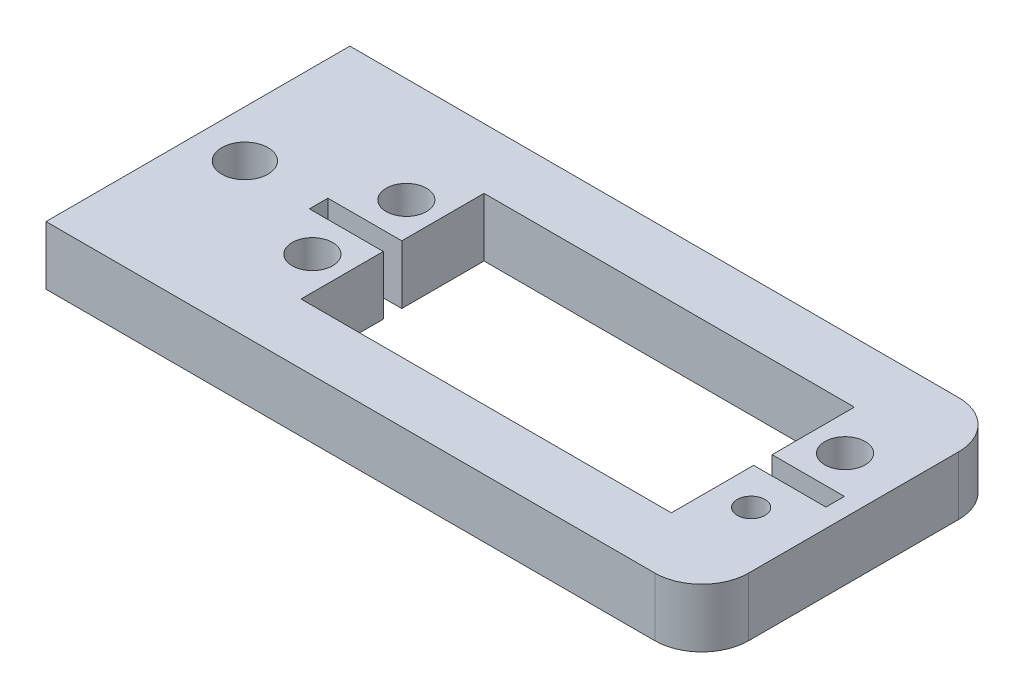
SolidWorks part; units mm, degrees
ref_plane "Front" through (0, 0, 0) normal (0, 0, 1) x (1, 0, 0)
ref_plane "Top" through (0, 0, 0) normal (0, 1, 0) x (1, 0, 0)
ref_plane "Right" through (0, 0, 0) normal (1, 0, 0) x (0, 0, -1)
sketch "Sketch1" plane through (0, 0, 0) normal (0, 1, 0) x (1, 0, 0)
  line L0 (-9.153, -1.4319) -> (-66.073, -1.4319)
  line L1 (-13.9032, -18.8819) -> (-13.9032, -27.7919)
  line L2 (-4.073, -6.5119) -> (-4.073, -29.2519)
  line L3 (-9.153, -34.3319) -> (-66.073, -34.3319)
  line L4 (-13.9032, -27.7919) -> (-54.0032, -27.7919)
  line L5 (-54.0032, -27.7919) -> (-54.0032, -18.8819)
  line L6 (-54.0032, -7.9719) -> (-13.9032, -7.9719)
  line L7 (-13.9032, -7.9719) -> (-13.9032, -16.8819)
  line L8 (-75.073, -29.2519) -> (-75.073, -6.5119)
  line L9 (-13.9032, -16.8819) -> (-6.073, -16.8819)
  line L10 (-54.0032, -16.8819) -> (-62.0032, -16.8819)
  line L11 (-13.9032, -18.8819) -> (-6.073, -18.8819)
  line L12 (-62.0032, -16.8819) -> (-62.0032, -18.8819)
  line L13 (-62.0032, -18.8819) -> (-54.0032, -18.8819)
  line L14 (-54.0032, -16.8819) -> (-54.0032, -7.9719)
  line L15 (-6.073, -16.8819) -> (-6.073, -18.8819)
  line L16 (-75.073, -17.8819) -> (-4.073, -17.8819) construction
  line L17 (-75.073, -6.5119) -> (-75.073, -1.4319)
  line L18 (-75.073, -1.4319) -> (-66.073, -1.4319)
  line L19 (-75.073, -29.2519) -> (-75.073, -34.3319)
  line L20 (-75.073, -34.3319) -> (-66.073, -34.3319)
  circle A0 centre (-57.5932, -22.9669) radius 2.19
  circle A1 centre (-57.5932, -12.7969) radius 2.19
  circle A2 centre (-10.0932, -12.7969) radius 2.19
  circle A3 centre (-69.9914, -17.8819) radius 2.5
  arc A4 (-4.073, -29.2519) -> (-9.153, -34.3319) centre (-9.153, -29.2519) cw
  arc A5 (-9.153, -1.4319) -> (-4.073, -6.5119) centre (-9.153, -6.5119) cw
  circle A6 centre (-10.0932, -22.9669) radius 1.5
  dimension "D1" = 22.74
extrude "Boss-Extrude1" add sketch "Sketch1" along normal blind 6.35
